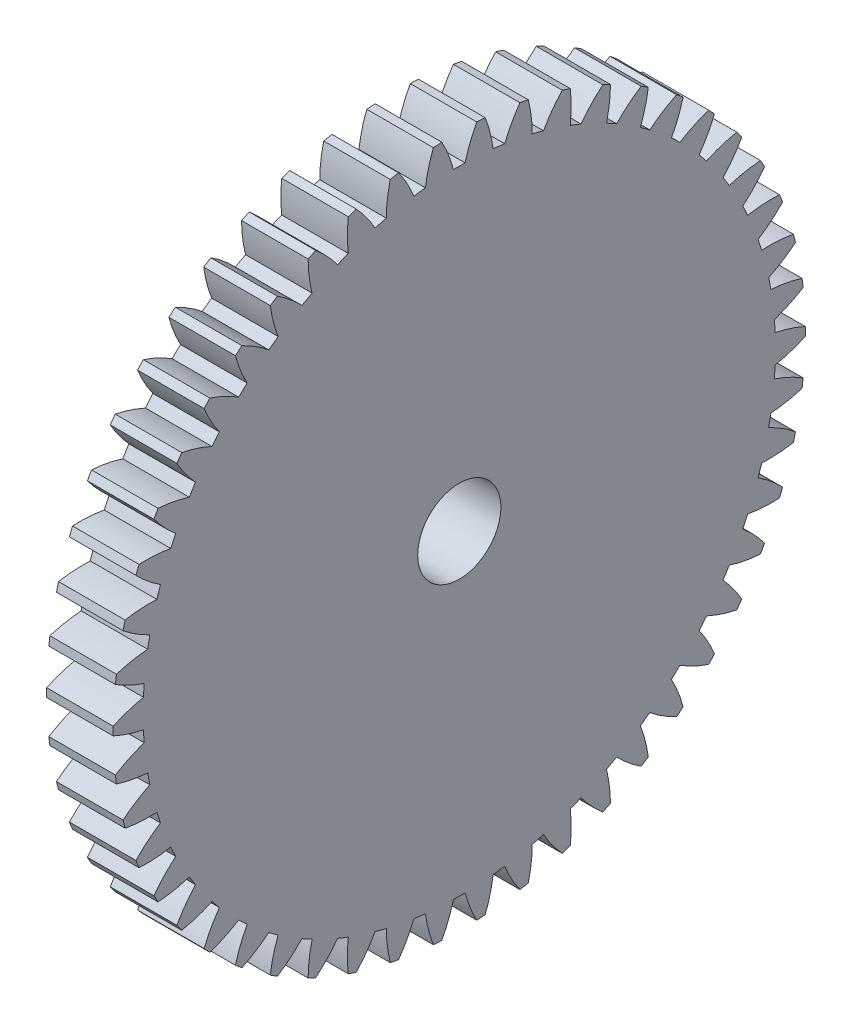
SolidWorks part; units mm, degrees
ref_plane "Plane1" through (0, 0, 0) normal (0, 0, 1) x (1, 0, 0)
ref_plane "Plane2" through (0, 0, 0) normal (0, 1, 0) x (1, 0, 0)
ref_plane "Plane3" through (0, 0, 0) normal (1, 0, 0) x (0, 0, -1)
sketch "HoldingSke" plane through (0, 0, 0) normal (0, 1, 0) x (1, 0, 0)
  line L0 (0, 0) -> (0.8035, -0.9576)
  line L1 (-15, 0) -> (100, 0) construction
  line L2 (0, 0) -> (-2.1039, 2.3779)
  line L3 (0, 0) -> (-11.863, 4.5341)
  line L4 (0, 0) -> (5.5511, 6.6156)
  line L5 (0, 0) -> (-46.8476, -17.4728)
  line L6 (0, 0) -> (-3.3159, -2.2372)
  line L7 (-2.1039, 2.3779) -> (8.6586, 51.2059)
  line L8 (-76.2, 54.61) -> (-75.3, 54.61)
  line L9 (-71.009, 38.7566) -> (-53.1078, 45.2721)
  line L10 (-76.2, 71.12) -> (104.1128, 71.12)
  line L11 (0, 0) -> (-4, 0)
  line L12 (-76.2, 101.6) -> (-76.17, 101.6)
  line L13 (24.9733, 27.94) -> (52.9518, 28.4284)
  line L14 (24.9733, 27.94) -> (24.9743, 27.94)
  line L15 (24.9733, 27.94) -> (100.4006, 29.5858)
  line L16 (-63.627, -0.8) -> (-12.827, -0.8)
  circle A0 centre (0, 0) radius 2.5
  circle A1 centre (0, 0) radius 18.999
  circle A2 centre (0, 0) radius 37.5
  circle A3 centre (0, 0) radius 2.5
  dimension "MHD" = 37.998
  dimension "Hub_dia" = 75
  dimension "Bore" = 5
  dimension "MBD" = 5
  dimension "Num_teeth" = 50
  dimension "Pitch" = 1.25
  dimension "Overall_len" = 50
  dimension "Show_teeth" = 50
  dimension "Thickness" = 4
  dimension "OAL" = 50.0001
  dimension "T_dim" = 0.9
  dimension "Ap" = 20
  dimension "H" = 19.05
  dimension "Pitch_radius" = 180.3128
  dimension "Width" = 4
  dimension "Backlash" = 0.03
  dimension "Addendum_fac" = 1
  dimension "Dedendum_fac" = 1.25
  dimension "Clearance_fac" = 0.25
  dimension "Dedendum_add" = 0.001
  dimension "Module" = 0.8
sketch "BasProSke" plane through (0, 0, 0) normal (0, 1, 0) x (1, 0, 0)
  line L0 (-10, 0) -> (60, 0) construction
  line L1 (0, 0) -> (0, 20.8)
  line L2 (0, 0) -> (4, 0)
  line L3 (4, 0) -> (4, 20.8)
  line L4 (4, 20.8) -> (0, 20.8)
  dimension "Thickness" = 4
  dimension "Diameter" = 41.6
revolve "Base-Revolve" add sketch "BasProSke" angle 360 about L0
sketch "TooCutSke" plane through (0, 0, 0) normal (1, 0, 0) x (0, 0, -1)
  line L1 (0, 0) -> (0, 107) construction
  line L2 (0, 0) -> (-0.6807, 19.9884) construction
  line L3 (0, 0) -> (-2.5106, 39.9045) construction
  line L4 (-0.6807, 19.9884) -> (-1.2553, 19.9523) construction
  arc A0 (0.3494, 18.9958) -> (-0.3494, 18.9958) centre (0, 0) ccw
  arc A1 (1.0655, 20.7981) -> (-1.0655, 20.7981) centre (0, 0) ccw
  circle A2 centre (0, 0) radius 20 construction
  circle A3 centre (0, 0) radius 18.7939 construction
  arc A4 (-0.3494, 18.9958) -> (-1.0655, 20.7981) centre (-8.0873, 16.9648) ccw
  arc A5 (1.0655, 20.7981) -> (0.3494, 18.9958) centre (8.0873, 16.9648) ccw
  dimension "Root_dia" = 37.998
  dimension "Overcut_dia" = 41.6508
  dimension "Pitch_dia" = 40
  dimension "Base_dia" = 37.5877
  dimension "Flank_rad" = 8
  dimension "Half_ang" = 3.6
  dimension "Half_CT" = 0.5757
extrude "ToothCut" cut sketch "TooCutSke" along normal through all
fillet "Breaks" [suppressed] radius 0.016
fillet "RootFillets" [suppressed] radius 0.201
pattern_circular "TeethCuts" count 50 every 7.2 about axis through (-10, 0, 0) along (1, 0, 0) of "ToothCut", "RootFillets", "Breaks"
sketch "HubNeaOneSke" plane through (0, 0, 0) normal (-1, 0, 0) x (0, 0, 1)
  circle A0 centre (0, 0) radius 18.999
  dimension "Diameter" = 37.998
extrude "HubNearOne" [suppressed] add sketch "HubNeaOneSke" along normal blind 46.0001
sketch "HubNeaBotSke" plane through (0, 0, 0) normal (-1, 0, 0) x (0, 0, 1)
  circle A0 centre (0, 0) radius 18.999
  dimension "Diameter" = 37.998
extrude "HubNearBoth" [suppressed] add sketch "HubNeaBotSke" along normal blind 23
ref_plane "FarPln" through (4, 0, 0) normal (1, 0, 0) x (0, 0, -1)
sketch "HubFarSke" plane through (4, 0, 0) normal (1, 0, 0) x (0, 0, -1)
  circle A0 centre (0, 0) radius 18.999
  dimension "Diameter" = 37.998
extrude "HubFar" [suppressed] add sketch "HubFarSke" along normal blind 23
sketch "BorSke" plane through (0, 0, 0) normal (1, 0, 0) x (0, 0, -1)
  circle A0 centre (0, 0) radius 2.5
  dimension "Diameter" = 5
extrude "Bore" cut sketch "BorSke" along normal mid plane 100.0001
sketch "KeySke" plane through (0, 0, 0) normal (1, 0, 0) x (0, 0, -1)
  line L0 (-1, 0) -> (-1, 3.4)
  line L1 (-1, 3.4) -> (1, 3.4)
  line L2 (1, 3.4) -> (1, 0)
  line L3 (0, 0) -> (0, 34) construction
  line L4 (-1, 0) -> (1, 0)
  dimension "Offset" = 3.4
  dimension "Width" = 2
extrude "Keyway" [suppressed] cut sketch "KeySke" along normal mid plane 100.0001
pattern_circular "Keyway2" [suppressed] count 2 every 90 about axis through (-10, 0, 0) along (1, 0, 0)
equation "' \"Module@HoldingSke\" = 6.35"
equation "' \"Num_teeth@HoldingSke\" = 12"
equation "' \"Ap@HoldingSke\" =  20"
equation "' \"Ap@HoldingSke\" = 20"
equation "' \"Width@HoldingSke\" = 0.5 * 25.4"
equation "' \"Hub_dia@HoldingSke\"= 1 * 25.4"
equation "' \"Hub_dia@HoldingSke\" = 1 * 25.4"
equation "' \"Overall_len@HoldingSke\" = 1.0 * 25.4"
equation "' \"Bore@HoldingSke\" = 0.75 * 25.4"
equation "' \"T_dim@HoldingSke\" = 0.1 * 25.4"
equation "' \"Width@KeySke\" = 0.25 * 25.4"
equation "' \"Show_teeth@HoldingSke\" = 13"
equation "' \"Backlash@HoldingSke\" = 0.009 * 25.4"
equation "' \"Addendum_fac@HoldingSke\" = 1.0"
equation "' \"Dedendum_fac@HoldingSke\" = 1.25"
equation "' \"Dedendum_add@HoldingSke\" = 0.00005 * 25.4"
equation "' \"Clearance_fac@HoldingSke\" = 0.25"
equation "\"Pitch@HoldingSke\" = 1 / \"Module@HoldingSke\""
equation "\"Overcut_dia@TooCutSke\" = (\"Num_teeth@HoldingSke\" + 2 * \"Addendum_fac@HoldingSke\") / \"Pitch@HoldingSke\" + 0.002 * 25.4"
equation "\"Pitch_dia@TooCutSke\" = \"Num_teeth@HoldingSke\" / \"Pitch@HoldingSke\""
equation "\"Base_dia@TooCutSke\" = \"Num_teeth@HoldingSke\" / \"Pitch@HoldingSke\" * cos((\"Ap@HoldingSke\"  * 3.14159265 / 180))"
equation "\"Root_dia@TooCutSke\" = (\"Num_teeth@HoldingSke\" + 2) / \"Pitch@HoldingSke\" - 2 * (\"Addendum_fac@HoldingSke\" + \"Dedendum_fac@HoldingSke\") / \"Pitch@HoldingSke\" - \"Dedendum_add@HoldingSke\" * 2"
equation "\"Half_ang@TooCutSke\" = 180 / \"Num_teeth@HoldingSke\""
equation "\"Half_CT@TooCutSke\" = \"Num_teeth@HoldingSke\" / \"Pitch@HoldingSke\" * sin((3.14159265 / 2 / \"Num_teeth@HoldingSke\")) / 2 - 7 * \"Backlash@HoldingSke\" / 4"
equation "\"Flank_rad@TooCutSke\" = \"Num_teeth@HoldingSke\" / \"Pitch@HoldingSke\" / 5"
equation "\"Radius@RootFillets\" = \"Clearance_fac@HoldingSke\" / \"Pitch@HoldingSke\" + \"Dedendum_add@HoldingSke\""
equation "\"Break_rad@Breaks\" = 0.02 / \"Pitch@HoldingSke\""
equation "\"Thickness@HoldingSke\" = \"Width@HoldingSke\""
equation "\"OAL@HoldingSke\" = \"Thickness@HoldingSke\""
equation "\"MHD@HoldingSke\" = (\"Num_teeth@HoldingSke\" + 2) / \"Pitch@HoldingSke\" - 2 * (\"Addendum_fac@HoldingSke\" + \"Dedendum_fac@HoldingSke\")  / \"Pitch@HoldingSke\" - \"Dedendum_add@HoldingSke\" * 2"
equation "\"MBD@HoldingSke\" = (\"Num_teeth@HoldingSke\" + 2) / \"Pitch@HoldingSke\" - 2 * (\"Addendum_fac@HoldingSke\" + \"Dedendum_fac@HoldingSke\")  / \"Pitch@HoldingSke\" - \"Dedendum_add@HoldingSke\" * 2 - 0.002 * 25.4"
equation "\"MHD@HoldingSke\" = ((sgn( \"MHD@HoldingSke\" - \"Hub_dia@HoldingSke\" )-1)*( \"MHD@HoldingSke\" - \"Hub_dia@HoldingSke\" ))/-2+ \"Hub_dia@HoldingSke\""
equation "\"MBD@HoldingSke\" = ((sgn( \"MBD@HoldingSke\" - \"Bore@HoldingSke\" )-1)*( \"MBD@HoldingSke\" - \"Bore@HoldingSke\" ))/-2+ \"Bore@HoldingSke\""
equation "\"OAL@HoldingSke\" = ((sgn( \"OAL@HoldingSke\" - \"Overall_len@HoldingSke\" )+1)*( \"OAL@HoldingSke\" - \"Overall_len@HoldingSke\" ))/2 + \"Overall_len@HoldingSke\" + 0.000002 * 25.4"
equation "\"Num_teeth@TeethCuts\" = int( \"Show_teeth@HoldingSke\" ) + 1"
equation "\"Num_teeth@TeethCuts\" = ((sgn( \"Num_teeth@TeethCuts\" - \"Num_teeth@HoldingSke\" )-1)*( \"Num_teeth@TeethCuts\" - \"Num_teeth@HoldingSke\" ))/-2+ \"Num_teeth@HoldingSke\""
equation "\"Num_teeth@TeethCuts\" = ((sgn( \"Num_teeth@TeethCuts\" - 2.0)+1)*( \"Num_teeth@TeethCuts\" - 2.0))/2 +2.0"
equation "\"Angle@TeethCuts\" = 360.0 / \"Num_teeth@HoldingSke\""
equation "\"Diameter@BasProSke\" = (\"Num_teeth@HoldingSke\" + 2 * \"Addendum_fac@HoldingSke\") / \"Pitch@HoldingSke\""
equation "\"Thickness@BasProSke\"  = \"Thickness@HoldingSke\""
equation "' \"Fillet_rad@BasProSke\" =  \"Thickness@HoldingSke\" * 0.05"
equation "' \"Fillet_rad@BasProSke\" = \"Thickness@HoldingSke\" * 0.05"
equation "\"MHD@HoldingSke\" = ((sgn( \"MHD@HoldingSke\" - \"Root_dia@TooCutSke\" )-1)*( \"MHD@HoldingSke\" - \"Root_dia@TooCutSke\" ))/-2+ \"Root_dia@TooCutSke\""
equation "\"Diameter@HubNeaOneSke\" = \"MHD@HoldingSke\""
equation "\"Length@HubNearOne\" = \"OAL@HoldingSke\" - \"Thickness@BasProSke\""
equation "\"Diameter@HubNeaBotSke\" = \"MHD@HoldingSke\""
equation "\"Length@HubNearBoth\" = ( \"OAL@HoldingSke\" - \"Thickness@BasProSke\" ) / 2.0"
equation "\"Thickness@FarPln\" = \"Thickness@BasProSke\""
equation "\"Diameter@HubFarSke\" = \"MHD@HoldingSke\""
equation "\"Length@HubFar\" = ( \"OAL@HoldingSke\" - \"Thickness@BasProSke\" ) / 2.0"
equation "\"Diameter@BorSke\" = \"MBD@HoldingSke\""
equation "\"D1@Bore\" = \"OAL@HoldingSke\" * 2.0"
equation "\"D1@Keyway\" = \"OAL@HoldingSke\" * 2.0"
equation "\"Offset@KeySke\" = \"T_dim@HoldingSke\" + \"MBD@HoldingSke\" / 2.0"
